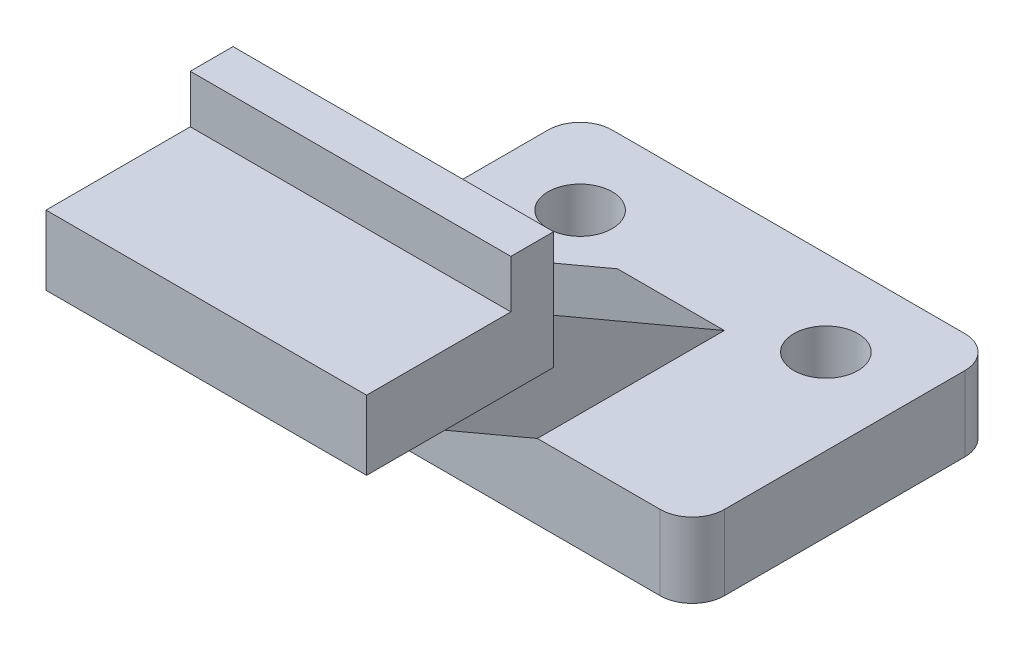
SolidWorks part; units mm, degrees
ref_plane "Piano frontale" through (0, 0, 0) normal (0, 0, 1) x (1, 0, 0)
ref_plane "Piano superiore" through (0, 0, 0) normal (0, 1, 0) x (1, 0, 0)
ref_plane "Piano destro" through (0, 0, 0) normal (1, 0, 0) x (0, 0, -1)
sketch "Schizzo1" plane through (0, 0, 0) normal (1, 0, 0) x (0, 0, -1)
  line L0 (-57, 0) -> (0, 0)
  line L1 (0, 0) -> (0, 14)
  line L2 (0, 14) -> (-22, 14)
  line L3 (-22, 14) -> (-73.9615, 44)
  line L4 (-73.9615, 44) -> (-73.9615, 66)
  line L5 (-73.9615, 66) -> (-81.9615, 66)
  line L6 (-81.9615, 66) -> (-81.9615, 57)
  line L7 (-81.9615, 57) -> (-108.9615, 57)
  line L8 (-108.9615, 57) -> (-108.9615, 44)
  line L11 (-57, 0) -> (-57, 14)
  line L12 (-57, 14) -> (-108.9615, 44)
  dimension "D1" = 14
  dimension "D2" = 57
  dimension "D3" = 30
  dimension "D4" = 13
  dimension "D5" = 22
  dimension "D6" = 8
  dimension "D7" = 35
  dimension "D8" = 22
  dimension "D9" = 150
extrude "Estrusione-Estrusione1" add sketch "Schizzo1" against normal blind 78 contours L3 L4 L5 L6 L7 L8 L12 L11 L0 L1 L2
sketch "Schizzo2" plane through (0, 0, 0) normal (1, 0, 0) x (0, 0, -1)
  line L0 (-22, 14) -> (-57, 14)
  line L1 (-57, 0) -> (-57, 14) construction
  line L2 (-57, 14) -> (-108.9615, 44)
  line L3 (-57, 14) -> (-108.9615, 44) construction
  line L4 (-108.9615, 44) -> (-73.9615, 44)
  line L5 (-73.9615, 44) -> (-22, 14)
extrude "Taglio-Estrusione1" cut sketch "Schizzo2" against normal blind 29
sketch "Schizzo3" plane through (-78, 0, 0) normal (-1, 0, 0) x (0, 0, 1)
  line L0 (57, 14) -> (22, 14)
  line L1 (0, 14) -> (22, 14) construction
  line L2 (22, 14) -> (73.9615, 44)
  line L3 (22, 14) -> (73.9615, 44) construction
  line L4 (73.9615, 44) -> (108.9615, 44)
  line L5 (108.9615, 44) -> (57, 14)
extrude "Taglio-Estrusione2" cut sketch "Schizzo3" against normal blind 29
sketch "Schizzo4" plane through (-78, 0, 0) normal (-1, 0, 0) x (0, 0, 1)
  line L0 (73.9615, 44) -> (73.9615, 66) construction
  line L1 (73.9615, 66) -> (108.9615, 66)
  line L2 (73.9615, 66) -> (73.9615, 44)
  line L3 (73.9615, 44) -> (108.9615, 44)
  line L4 (108.9615, 66) -> (108.9615, 44)
  dimension "D1" = 22
extrude "Taglio-Estrusione3" cut sketch "Schizzo4" against normal blind 9
sketch "Schizzo5" plane through (0, 0, 0) normal (1, 0, 0) x (0, 0, -1)
  line L1 (-108.9615, 44) -> (-73.9615, 44)
  line L2 (-108.9615, 44) -> (-108.9615, 66)
  line L3 (-108.9615, 66) -> (-73.9615, 66)
  line L4 (-73.9615, 44) -> (-73.9615, 66)
extrude "Taglio-Estrusione4" cut sketch "Schizzo5" against normal blind 9
sketch "Schizzo6" plane through (0, 14, 0) normal (0, 1, 0) x (1, 0, 0)
  line L0 (-78, 0) -> (0, 0) construction
  line L1 (0, 0) -> (0, -57) construction
  line L2 (-78, 0) -> (-78, -57) construction
  circle A0 centre (-16, -16) radius 6
  circle A1 centre (-62, -16) radius 6
  point P6 (0, 0)
  dimension "D4" = 12
  dimension "D1" = 16
  dimension "D2" = 16
  dimension "D3" = 16
extrude "Taglio-Estrusione5" cut sketch "Schizzo6" against normal through all
fillet "Raccordo1" radius 6 4 edges at (-78, 7, 0) (-78, 7, 57) (0, 7, 57) (0, 7, 0)
